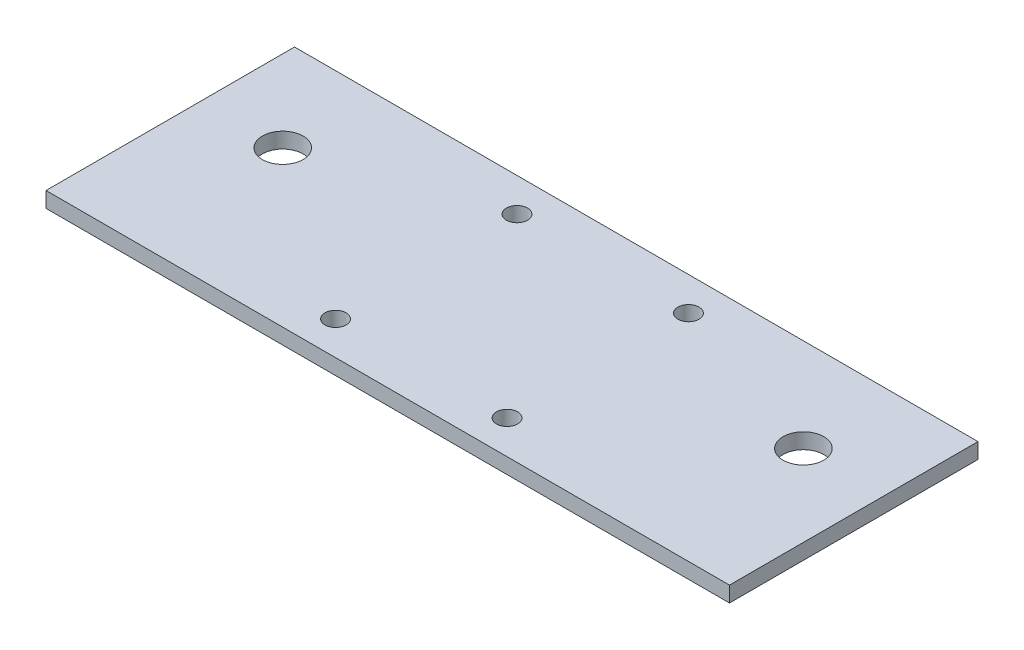
SolidWorks part; units mm, degrees
material "6061-T6 (SS)"
ref_plane "Front Plane" through (0, 0, 0) normal (0, 0, 1) x (1, 0, 0)
ref_plane "Top Plane" through (0, 0, 0) normal (0, 1, 0) x (1, 0, 0)
ref_plane "Right Plane" through (0, 0, 0) normal (1, 0, 0) x (0, 0, -1)
sketch "Sketch1" plane through (0, 0, 0) normal (0, 1, 0) x (1, 0, 0)
  line L0 (0, 0) -> (0, -37.084) construction
  line L1 (0, 0) -> (35.052, 0) construction
  line L2 (35.052, 0) -> (35.052, -37.084) construction
  line L3 (35.052, -37.084) -> (0, -37.084) construction
  line L5 (-52.324, 6.858) -> (87.376, 6.858)
  line L6 (-52.324, 6.858) -> (-52.324, -43.942)
  line L7 (-52.324, -43.942) -> (87.376, -43.942)
  line L8 (87.376, 6.858) -> (87.376, -43.942)
  circle A0 centre (0, 0) radius 2.159
  circle A1 centre (35.052, 0) radius 2.159
  circle A2 centre (0, -37.084) radius 2.159
  circle A3 centre (35.052, -37.084) radius 2.159
  circle A4 centre (-35.687, -12.192) radius 4.1656
  circle A5 centre (70.739, -12.192) radius 4.1656
  dimension "D1" = 4.318
  dimension "D2" = 4.318
  dimension "D3" = 4.318
  dimension "D4" = 4.318
  dimension "D15" = 8.3312
  dimension "D16" = 8.3312
  dimension "D5" = 35.052
  dimension "D6" = 35.052
  dimension "D7" = 37.084
  dimension "D8" = 37.084
  dimension "D9" = 139.7
  dimension "D10" = 50.8
  dimension "D11" = 6.858
  dimension "D12" = 52.324
  dimension "D13" = 16.637
  dimension "D14" = 19.05
  dimension "D17" = 16.637
  dimension "D18" = 19.05
extrude "Boss-Extrude1" add sketch "Sketch1" along normal blind 3.175
